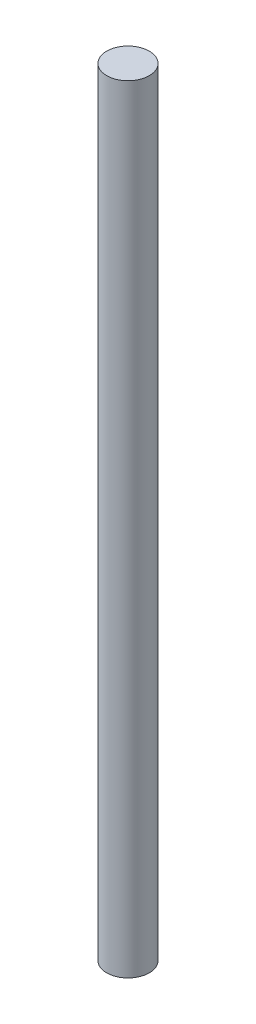
SolidWorks part; units mm, degrees
ref_plane "Front Plane" through (0, 0, 0) normal (0, 0, 1) x (1, 0, 0)
ref_plane "Top Plane" through (0, 0, 0) normal (0, 1, 0) x (1, 0, 0)
ref_plane "Right Plane" through (0, 0, 0) normal (1, 0, 0) x (0, 0, -1)
sketch "Sketch1" plane through (0, 0, 0) normal (0, 1, 0) x (1, 0, 0)
  circle A0 centre (0, 0) radius 2
  dimension "D1" = 4
extrude "Boss-Extrude1" add sketch "Sketch1" along normal blind 73
